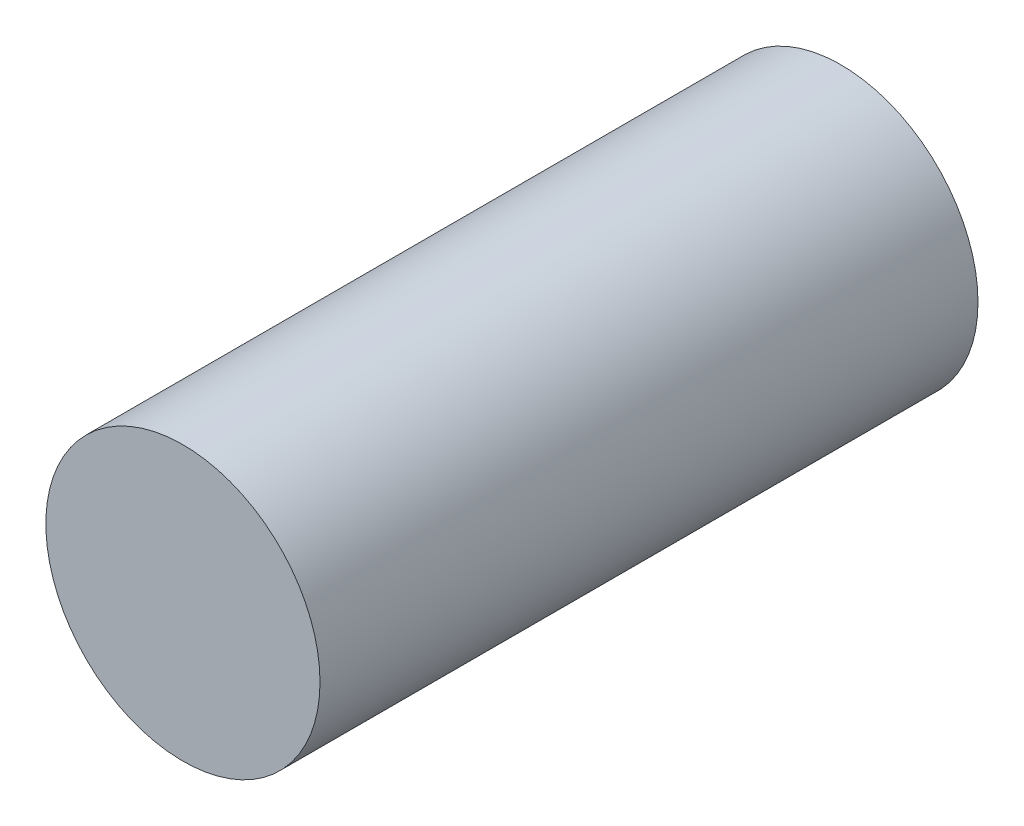
SolidWorks part; units mm, degrees
ref_plane "前视基准面" through (0, 0, 0) normal (0, 0, 1) x (1, 0, 0)
ref_plane "上视基准面" through (0, 0, 0) normal (0, 1, 0) x (1, 0, 0)
ref_plane "右视基准面" through (0, 0, 0) normal (1, 0, 0) x (0, 0, -1)
other "Configuration Table"
sketch "草图1" plane through (0, 0, 0) normal (0, 0, 1) x (1, 0, 0)
  circle A0 centre (0, 0) radius 5
extrude "凸台-拉伸1" add sketch "草图1" along normal blind 24
